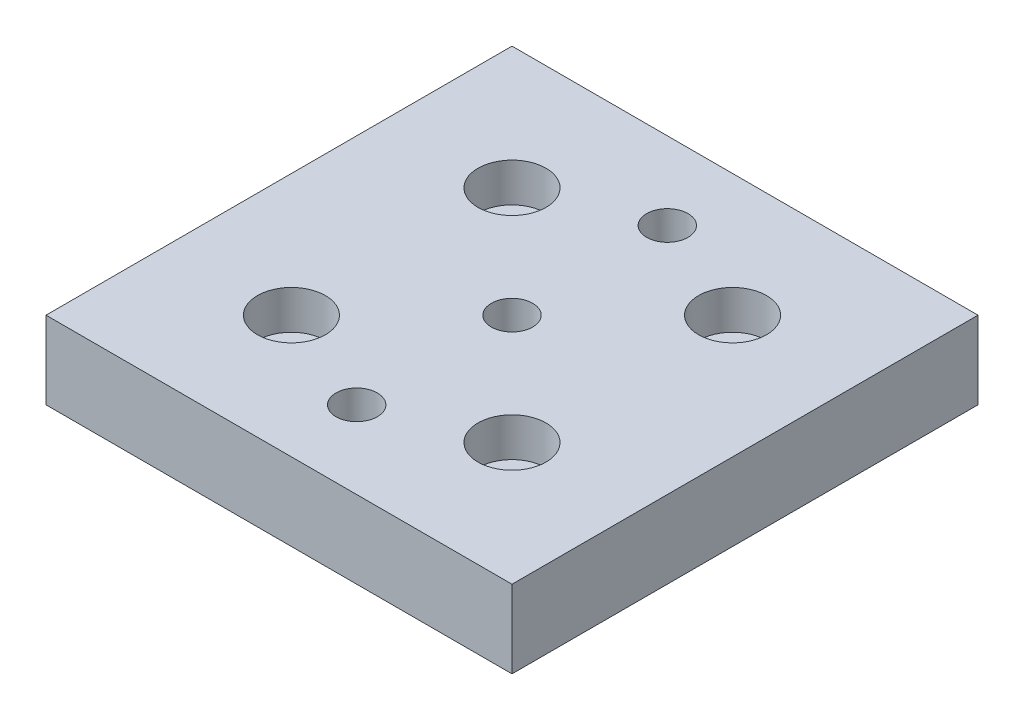
SolidWorks part; units mm, degrees
ref_plane "Front Plane" through (0, 0, 0) normal (0, 0, 1) x (1, 0, 0)
ref_plane "Top Plane" through (0, 0, 0) normal (0, 1, 0) x (1, 0, 0)
ref_plane "Right Plane" through (0, 0, 0) normal (1, 0, 0) x (0, 0, -1)
sketch "Sketch1" plane through (0, 0, 0) normal (0, 1, 0) x (1, 0, 0)
  line L1 (-38.1, -38.1) -> (38.1, -38.1)
  line L2 (-38.1, -38.1) -> (-38.1, 38.1)
  line L3 (-38.1, 38.1) -> (38.1, 38.1)
  line L4 (38.1, -38.1) -> (38.1, 38.1)
  line L5 (-38.1, -38.1) -> (38.1, 38.1) construction
  line L6 (-38.1, 38.1) -> (38.1, -38.1) construction
  point P0 (0, 0)
  dimension "D1" = 76.2
  dimension "D2" = 76.2
extrude "Boss-Extrude1" add sketch "Sketch1" along normal blind 12.7
hole_wizard "CBORE for 1/4 Socket Head Cap Screw2" positions "Sketch2" profile "Sketch3" counterbore size "1/4" standard "ANSI Inch" end condition through all
sketch "Sketch2" plane through (0, 12.7, 0) normal (0, 1, 0) x (1, 0, 0)
  point P0 (-18.034, 18.034)
  point P4 (18.034, 18.034)
  point P6 (18.034, -18.034)
  point P10 (-18.034, -18.034)
  dimension "D1" = 18.034
  dimension "D2" = 18.034
  dimension "D3" = 36.068
  dimension "D4" = 36.068
sketch "Sketch3" plane through (-18.034, 12.7, -18.034) normal (1, 0, 0) x (0, 0, 1)
  line L0 (0, 0) -> (0, 12.7)
  line L1 (0, 12.7) -> (3.3782, 12.7)
  line L3 (3.3782, 12.7) -> (3.3782, 6.35)
  line L4 (3.3782, 6.35) -> (5.5562, 6.35)
  line L5 (5.5562, 6.35) -> (5.5563, 0)
  line L7 (5.5563, 0) -> (0, 0)
  line L11 (0, -6.35) -> (0, 107.95) construction
  dimension "Thru Hole Dia." = 6.7564
  dimension "Thru Hole Depth" = 12.7
  dimension "C'Bore Dia." = 11.1125
  dimension "C'Bore Depth" = 6.35
hole_wizard "CBORE for 1/4 Socket Head Cap Screw1" positions "Sketch4" profile "Sketch5" counterbore size "1/4" standard "ANSI Inch" end condition through all
sketch "Sketch4" plane through (0, 0, 0) normal (0, -1, 0) x (-1, 0, 0)
  point P0 (0, 25.4)
  point P2 (0, 0)
  point P5 (0, -25.4)
  dimension "D1" = 25.4
  dimension "D2" = 25.4
sketch "Sketch5" plane through (0, 0, -25.4) normal (1, 0, 0) x (0, 0, -1)
  line L0 (0, 0) -> (0, 12.7)
  line L1 (0, 12.7) -> (3.3782, 12.7)
  line L3 (3.3782, 12.7) -> (3.3782, 6.35)
  line L4 (3.3782, 6.35) -> (5.5562, 6.35)
  line L5 (5.5562, 6.35) -> (5.5563, 0)
  line L7 (5.5563, 0) -> (0, 0)
  line L11 (0, -6.35) -> (0, 107.95) construction
  dimension "Thru Hole Dia." = 6.7564
  dimension "Thru Hole Depth" = 12.7
  dimension "C'Bore Dia." = 11.1125
  dimension "C'Bore Depth" = 6.35
